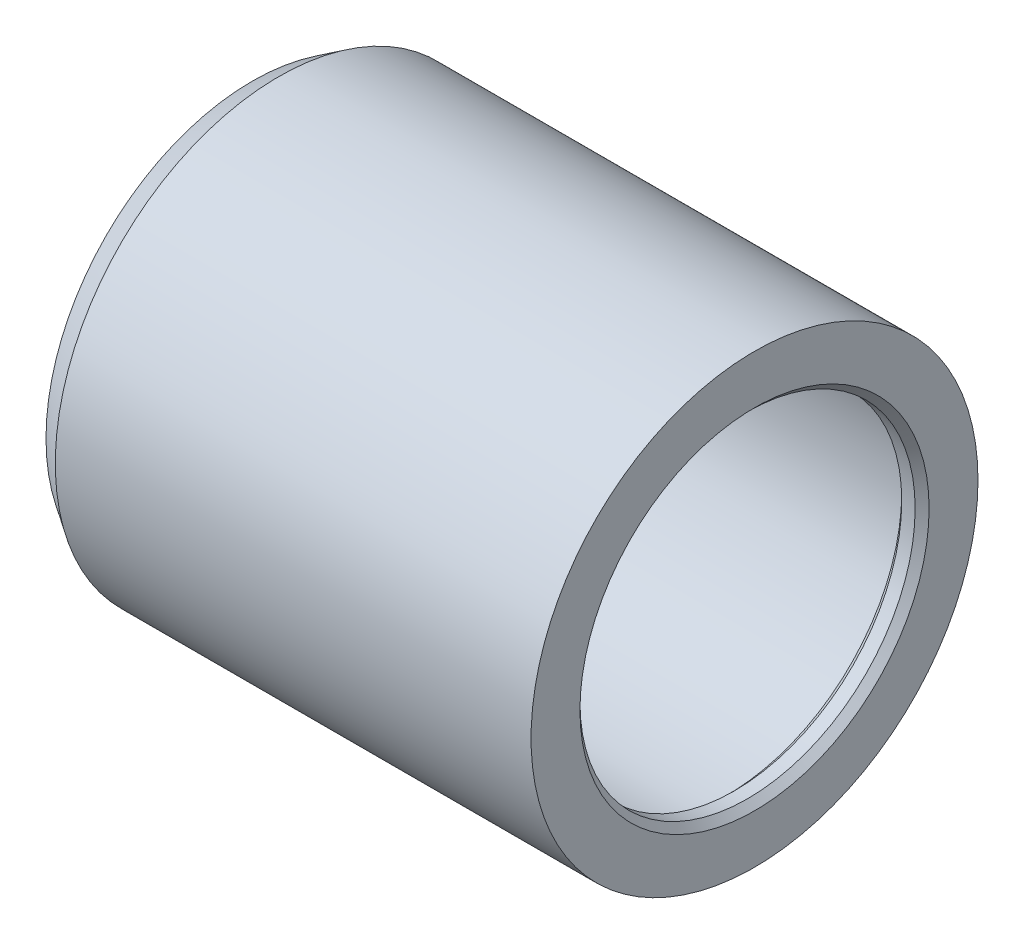
SolidWorks part; units mm, degrees
ref_plane "Alzado" through (0, 0, 0) normal (0, 0, 1) x (1, 0, 0)
ref_plane "Planta" through (0, 0, 0) normal (0, 1, 0) x (1, 0, 0)
ref_plane "Vista lateral" through (0, 0, 0) normal (1, 0, 0) x (0, 0, -1)
sketch "Sketch1" plane through (0, 0, 0) normal (0, 0, 1) x (1, 0, 0)
  line L0 (0, 0) -> (-53, 0) construction
  line L1 (-17.9798, 7.3839) -> (-17.0312, 8)
  line L4 (0, 6) -> (0, 8)
  line L19 (0, 8) -> (-17.0312, 8)
  line L21 (-17.9798, 7.3839) -> (-17.9798, 6.8881)
  line L22 (-17.9798, 6.8881) -> (-0.9798, 6.8881)
  line L23 (-0.9798, 6.8881) -> (-0.9798, 6)
  line L24 (-0.9798, 6) -> (0, 6)
  dimension "D1" = 6.8881
  dimension "D2" = 6
  dimension "D3" = 8
  dimension "D4" = 33
  dimension "D5" = 0.4959
  dimension "D6" = 17
revolve "Revolve1" add sketch "Sketch1" angle 360 about L0
chamfer "Chaflán10" distance 0.25 angle 45 3 edges at (-0.9798, 0, -6) (0, 0, -6) (-17.9798, 0, -6.8881)
